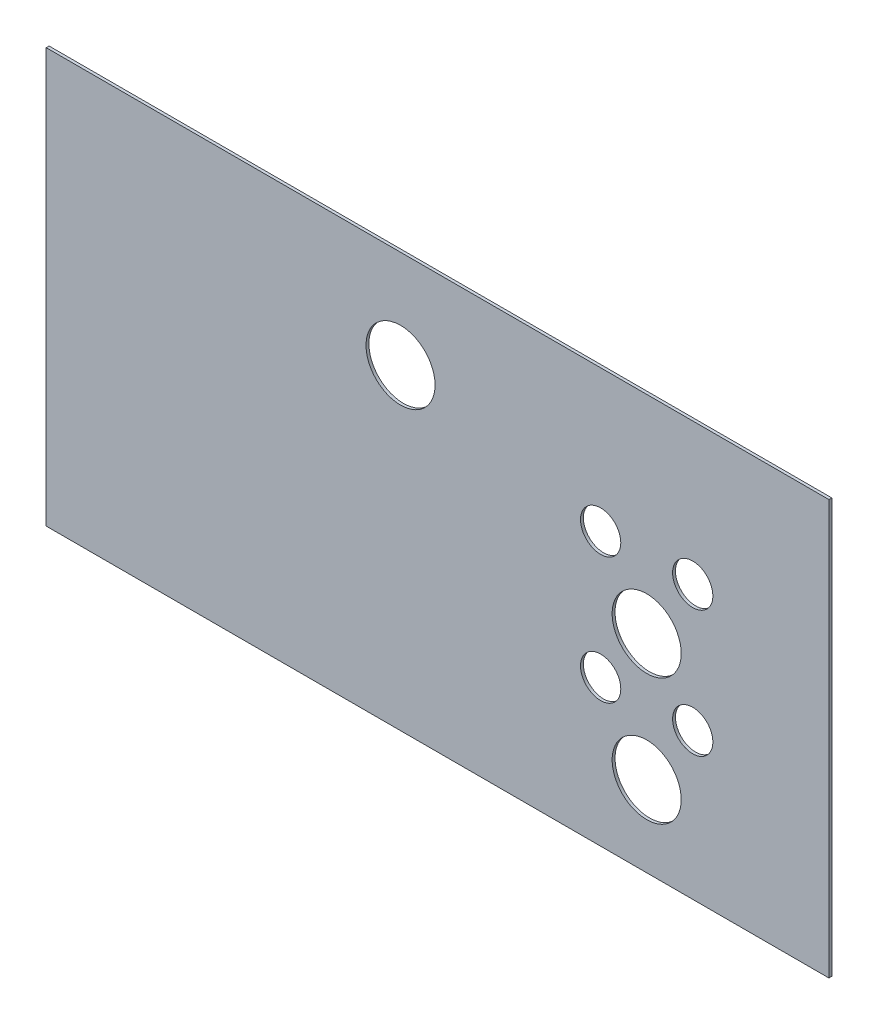
SolidWorks part; units mm, degrees
ref_plane "Front Plane" through (0, 0, 0) normal (0, 0, 1) x (1, 0, 0)
ref_plane "Top Plane" through (0, 0, 0) normal (0, 1, 0) x (1, 0, 0)
ref_plane "Right Plane" through (0, 0, 0) normal (1, 0, 0) x (0, 0, -1)
sketch "Sketch1" plane through (0, 0, 0) normal (0, 0, 1) x (1, 0, 0)
  line L0 (-431.8, 0) -> (431.8, 0) construction
  line L1 (-431.8, 228.6) -> (431.8, 228.6)
  line L2 (-431.8, 228.6) -> (-431.8, -228.6)
  line L3 (-431.8, -228.6) -> (431.8, -228.6)
  line L4 (431.8, 228.6) -> (431.8, -228.6)
  line L5 (0, 228.6) -> (0, -228.6) construction
  point P8 (0, 0)
  dimension "D1" = 863.6
  dimension "D2" = 457.2
extrude "Boss-Extrude1" add sketch "Sketch1" along normal blind 3.175
sketch "Sketch2" plane through (0, 0, 3.175) normal (0, 0, 1) x (1, 0, 0)
  circle A2 centre (230.7381, 0) radius 38.1
  circle A3 centre (230.7381, -139.7) radius 38.1
  circle A4 centre (179.9381, -67.2228) radius 22.225
  circle A5 centre (281.5381, -67.2228) radius 22.225
  circle A6 centre (179.9381, 72.4772) radius 22.225
  circle A7 centre (281.5381, 72.4772) radius 22.225
  circle A8 centre (-40.8559, 120.65) radius 38.1
  dimension "D1" = 76.2
  dimension "D2" = 76.2
  dimension "D3" = 76.2
  dimension "D4" = 44.45
extrude "Cut-Extrude1" cut sketch "Sketch2" against normal through all
